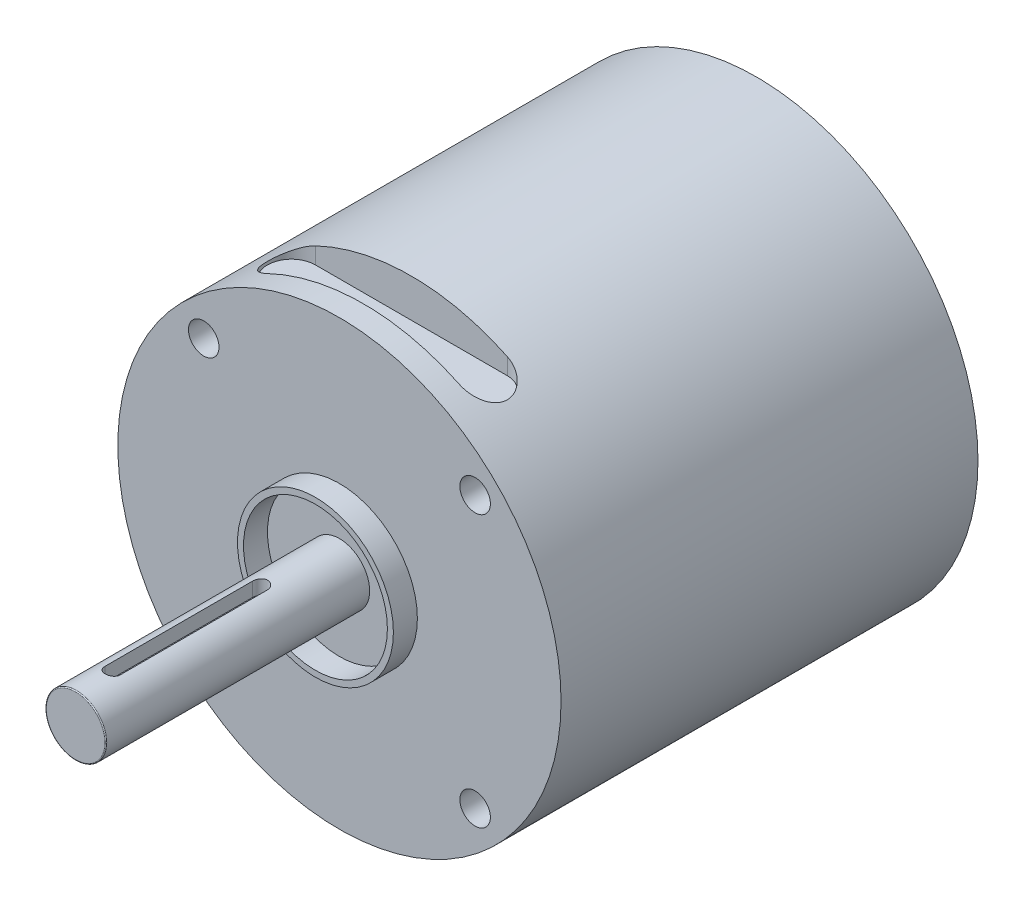
SolidWorks part; units mm, degrees
ref_plane "Front Plane" through (0, 0, 0) normal (0, 0, 1) x (1, 0, 0)
ref_plane "Top Plane" through (0, 0, 0) normal (0, 1, 0) x (1, 0, 0)
ref_plane "Right Plane" through (0, 0, 0) normal (1, 0, 0) x (0, 0, -1)
sketch "Sketch1" plane through (0, 0, 0) normal (0, 0, 1) x (1, 0, 0)
  circle A0 centre (0, 0) radius 29.337
  dimension "D1" = 58.674
extrude "Boss-Extrude1" add sketch "Sketch1" along normal blind 55.1942
sketch "Sketch2" plane through (0, 0, 55.1942) normal (0, 0, 1) x (1, 0, 0)
  circle A0 centre (0, 0) radius 9.525
  circle A1 centre (0, 0) radius 10.3187
  dimension "D1" = 19.05
  dimension "D2" = 20.6375
extrude "Boss-Extrude2" add sketch "Sketch2" along normal blind 3.175
sketch "Sketch3" plane through (0, 0, 55.1942) normal (0, 0, 1) x (1, 0, 0)
  circle A0 centre (0, 0) radius 4.0005
  dimension "D1" = 8.001
extrude "Boss-Extrude3" add sketch "Sketch3" along normal blind 34.925
sketch "Sketch4" plane through (0, 0, 55.1942) normal (0, 0, 1) x (1, 0, 0)
  line L1 (0, 0) -> (-52.3773, 0) construction
  line L2 (0, 0) -> (-17.9605, -17.9605) construction
  line L3 (0, 0) -> (17.9605, -17.9605) construction
  line L4 (0, 0) -> (17.9605, 17.9605) construction
  line L5 (0, 0) -> (-17.9605, 17.9605) construction
  circle A5 centre (0, 0) radius 25.4 construction
  circle A6 centre (17.9605, -17.9605) radius 2.0193
  circle A7 centre (-17.9605, -17.9605) radius 2.0193
  circle A8 centre (-17.9605, 17.9605) radius 2.0193
  circle A9 centre (17.9605, 17.9605) radius 2.0193
  dimension "D1" = 50.8
  dimension "D2" = 90
  dimension "D6" = 4.0386
  dimension "D3" = 90
  dimension "D4" = 45
  dimension "D5" = 90
extrude "Cut-Extrude1" cut sketch "Sketch4" against normal blind 12.7
ref_plane "Plane1" through (0, 29.337, 0) normal (0, 1, 0) x (1, 0, 0)
sketch "Sketch5" plane through (0, 29.337, 0) normal (0, 1, 0) x (1, 0, 0)
  line L0 (12.7, -48.8442) -> (-12.7, -48.8442) construction
  line L1 (12.7, -52.0192) -> (-12.7, -52.0192)
  line L2 (12.7, -45.6692) -> (-12.7, -45.6692)
  line L3 (-29.337, -55.1942) -> (29.337, -55.1942) construction
  line L4 (0, -90.1192) -> (0, 0) construction
  line L5 (-4.0005, -90.1192) -> (4.0005, -90.1192) construction
  arc A0 (12.7, -52.0192) -> (12.7, -45.6692) centre (12.7, -48.8442) ccw
  arc A1 (-12.7, -45.6692) -> (-12.7, -52.0192) centre (-12.7, -48.8442) ccw
  point P2 (0, -48.8442)
  dimension "D3" = 25.4
  dimension "D1" = 3.175
  dimension "D2" = 6.35
extrude "Cut-Extrude2" cut sketch "Sketch5" against normal blind 5.08
ref_plane "Plane2" through (0, 4.0005, 0) normal (0, 1, 0) x (1, 0, 0)
sketch "Sketch6" plane through (0, 4.0005, 0) normal (0, 1, 0) x (1, 0, 0)
  line L0 (0, -90.1192) -> (0, -58.3692) construction
  line L1 (-4.0005, -90.1192) -> (4.0005, -90.1192) construction
  line L2 (-10.3187, -58.3692) -> (10.3187, -58.3692) construction
  line L3 (0, -65.7187) -> (0, -85.2183) construction
  line L4 (0.9995, -65.7187) -> (0.9995, -85.2183)
  line L5 (-0.9995, -65.7187) -> (-0.9995, -85.2183)
  line L6 (-9.525, -58.3692) -> (9.525, -58.3692) construction
  arc A0 (0.9995, -65.7187) -> (-0.9995, -65.7187) centre (0, -65.7187) ccw
  arc A1 (-0.9995, -85.2183) -> (0.9995, -85.2183) centre (0, -85.2183) ccw
  point P8 (0, -75.4685)
  point P13 (0, -64.7192)
  dimension "D1" = 6.35
  dimension "D2" = 1.999
  dimension "D3" = 19.4996
extrude "Cut-Extrude3" cut sketch "Sketch6" against normal blind 2
fillet "Fillet1" radius 0.127 1 edges at (4.0005, 0, 90.1192)
